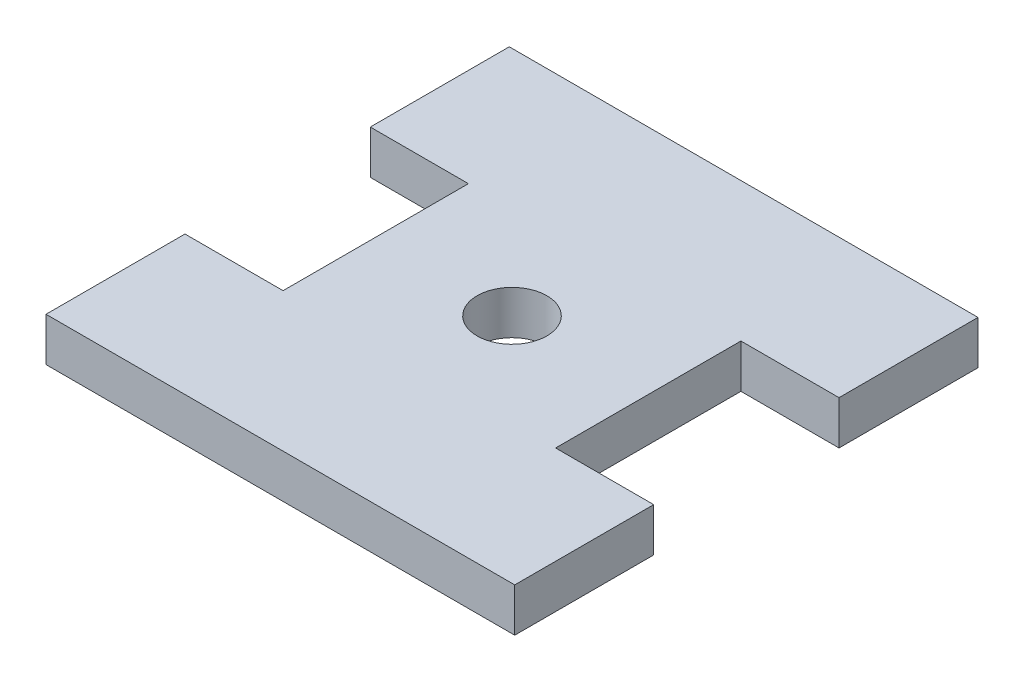
SolidWorks part; units mm, degrees
ref_plane "Спереди" through (0, 0, 0) normal (0, 0, 1) x (1, 0, 0)
ref_plane "Сверху" through (0, 0, 0) normal (0, 1, 0) x (1, 0, 0)
ref_plane "Справа" through (0, 0, 0) normal (1, 0, 0) x (0, 0, -1)
sketch "Эскиз1" plane through (0, 0, 0) normal (0, 1, 0) x (1, 0, 0)
  line L0 (15.3261, -63.1399) -> (58.3261, -20.6399) construction
  line L1 (15.3261, -20.6399) -> (58.3261, -20.6399)
  line L2 (15.3261, -20.6399) -> (15.3261, -63.1399)
  line L3 (15.3261, -63.1399) -> (58.3261, -63.1399)
  line L4 (58.3261, -20.6399) -> (58.3261, -63.1399)
  line L5 (15.3261, -20.6399) -> (58.3261, -63.1399) construction
  circle A0 centre (36.8261, -41.8899) radius 3.2
  dimension "D3" = 6.4
  dimension "D1" = 42.5
  dimension "D2" = 43
extrude "Бобышка-Вытянуть1" add sketch "Эскиз1" along normal blind 4
sketch "Эскиз2" plane through (0, 4, 0) normal (0, 1, 0) x (1, 0, 0)
  line L0 (36.8261, -20.6399) -> (36.8261, -63.1399) construction
  line L1 (58.3261, -20.6399) -> (15.3261, -20.6399) construction
  line L2 (15.3261, -63.1399) -> (58.3261, -63.1399) construction
  line L3 (36.8261, -63.1399) -> (15.3261, -41.8899) construction
  line L4 (15.3261, -20.6399) -> (15.3261, -63.1399) construction
  line L5 (15.3261, -41.8899) -> (58.3261, -41.8899) construction
  line L6 (58.3261, -63.1399) -> (58.3261, -20.6399) construction
  line L8 (15.3261, -33.3899) -> (24.3261, -33.3899)
  line L9 (15.3261, -33.3899) -> (15.3261, -50.3899)
  line L10 (15.3261, -50.3899) -> (24.3261, -50.3899)
  line L11 (24.3261, -33.3899) -> (24.3261, -50.3899)
  line L12 (58.3261, -33.3899) -> (49.3261, -33.3899)
  line L13 (58.3261, -33.3899) -> (58.3261, -50.3899)
  line L14 (58.3261, -50.3899) -> (49.3261, -50.3899)
  line L15 (49.3261, -33.3899) -> (49.3261, -50.3899)
  dimension "D1" = 25
  dimension "D2" = 9
  dimension "D3" = 17
  dimension "D4" = 17
  dimension "D5" = 8.5
  dimension "D6" = 8.5
extrude "Вырез-Вытянуть1" cut sketch "Эскиз2" against normal blind 4
